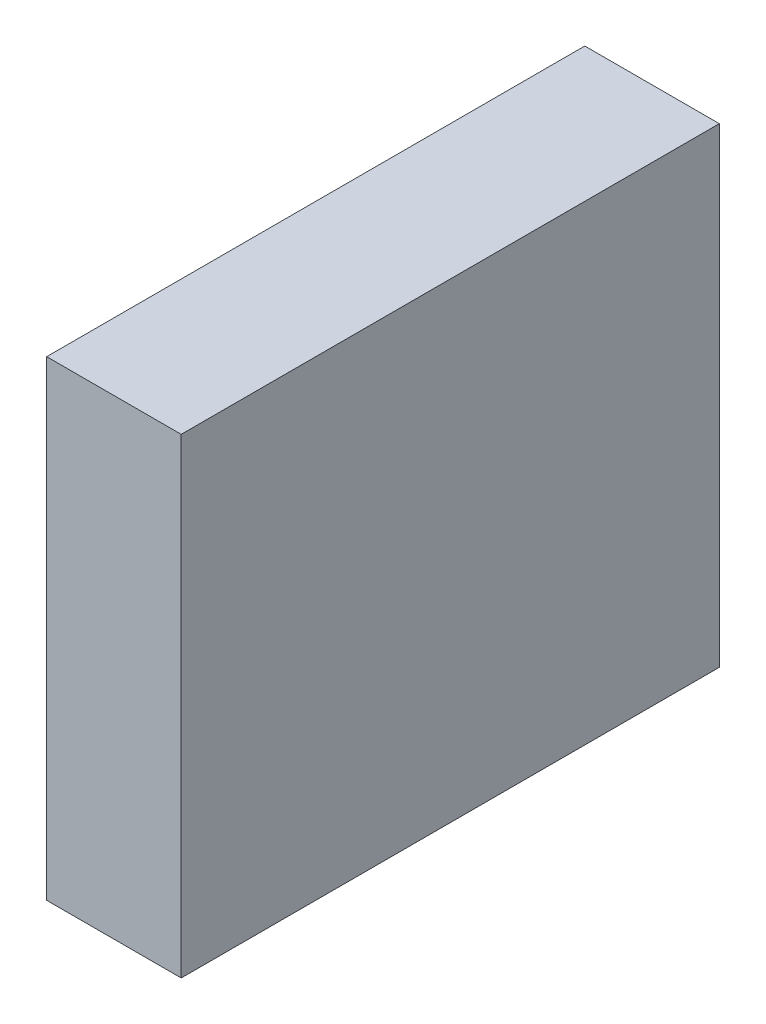
SolidWorks part; units mm, degrees
ref_plane "Front Plane" through (0, 0, 0) normal (0, 0, 1) x (1, 0, 0)
ref_plane "Top Plane" through (0, 0, 0) normal (0, 1, 0) x (1, 0, 0)
ref_plane "Right Plane" through (0, 0, 0) normal (1, 0, 0) x (0, 0, -1)
sketch "Sketch1" plane through (0, 0, 0) normal (0, 0, 1) x (1, 0, 0)
  line L1 (-5, 17.5) -> (5, 17.5)
  line L2 (-5, 17.5) -> (-5, -17.5)
  line L3 (-5, -17.5) -> (5, -17.5)
  line L4 (5, 17.5) -> (5, -17.5)
  line L5 (-5, 17.5) -> (5, -17.5) construction
  line L6 (-5, -17.5) -> (5, 17.5) construction
  point P0 (0, 0)
  dimension "D1" = 10
  dimension "D2" = 35
extrude "Boss-Extrude1" add sketch "Sketch1" along normal blind 40
hole_wizard "M3x0.5 Tapped Hole1" positions "Sketch2" profile "Sketch3" tap size "M3x0.5" standard "ANSI Metric"
sketch "Sketch2" plane through (0, 0, 0) normal (0, 0, -1) x (-1, 0, 0)
  point P0 (0, 11.3549)
  point P2 (0, -11.3987)
sketch "Sketch3" plane through (0, 11.3549, 0) normal (1, 0, 0) x (0, 1, 0)
  line L0 (0, 0) -> (0, 11.7511)
  line L1 (0, 11.7511) -> (1.25, 11)
  line L2 (1.25, 11) -> (1.25, 0.275)
  line L3 (1.25, 0.275) -> (1.525, 0)
  line L5 (1.525, 0) -> (0, 0)
  line L6 (-1.25, 0.275) -> (-1.525, 0) construction
  line L10 (0, 11.7511) -> (-1.25, 11) construction
  line L11 (0, -6.35) -> (0, 107.95) construction
  dimension "Tap Drill Dia." = 2.5
  dimension "Tap Drill Depth" = 11
  dimension "Near C'Sink Dia." = 3.05
  dimension "Near C'Sink Angle" = 90
  dimension "Drill Angle" = 118
cosmetic thread "Hole Thread1" parameters "D1"=9.5, "D2"=3
cosmetic thread "Hole Thread2" parameters "D1"=9.5, "D2"=3
